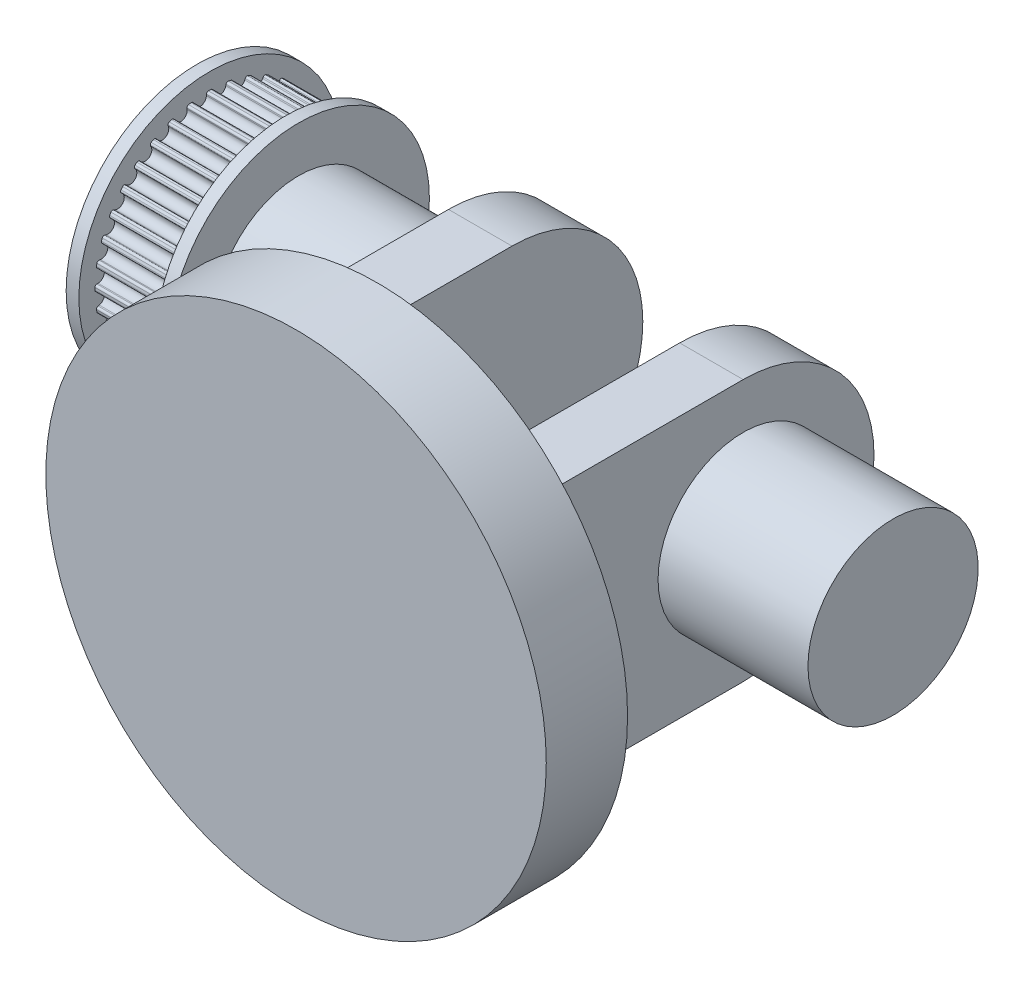
SolidWorks part; units mm, degrees
ref_plane "前视基准面" through (0, 0, 0) normal (0, 0, 1) x (1, 0, 0)
ref_plane "上视基准面" through (0, 0, 0) normal (0, 1, 0) x (1, 0, 0)
ref_plane "右视基准面" through (0, 0, 0) normal (1, 0, 0) x (0, 0, -1)
sketch "Sketch2" plane through (0, 0, 0) normal (0, 0, 1) x (1, 0, 0)
  line L2 (-58, -79.6131) -> (-58, 79.6131)
  line L4 (58, -79.6131) -> (58, 79.6131)
  line L5 (-58, -79.6131) -> (58, 79.6131) construction
  line L6 (-58, 79.6131) -> (58, -79.6131) construction
  arc A0 (-58, -79.6131) -> (58, -79.6131) centre (0, 0) ccw
  arc A1 (58, 79.6131) -> (-58, 79.6131) centre (0, 0) ccw
  dimension "D1" = 197
  dimension "D2" = 116
extrude "Extrude1" add sketch "Sketch2" along normal blind 32
sketch "Sketch3" plane through (-58, 0, 0) normal (-1, 0, 0) x (0, 0, 1)
  line L0 (-86, 0) -> (0, 0) construction
  line L1 (-86, 51.5) -> (0, 51.5)
  line L2 (0, 79.6131) -> (0, -79.6131) construction
  line L3 (0, 51.5) -> (0, -51.5)
  line L4 (0, -51.5) -> (-86, -51.5)
  circle A0 centre (-86, 0) radius 33.5 construction
  arc A1 (-86, 51.5) -> (-86, -51.5) centre (-86, 0) ccw
  dimension "D1" = 67
  dimension "D2" = 103
  dimension "D3" = 86
extrude "Extrude2" add sketch "Sketch3" against normal blind 25
sketch "Sketch4" plane through (-58, 0, 0) normal (-1, 0, 0) x (0, 0, 1)
  circle A0 centre (-86, 0) radius 33.5
  dimension "D1" = 67
extrude "Extrude3" add sketch "Sketch4" along normal blind 59
mirror "Mirror1" about plane through (0, 0, 0) normal (1, 0, 0) of "Extrude2", "Extrude3"
sketch "Sketch5" plane through (-117, 0, 0) normal (1, 0, 0) x (0, 0, -1)
  circle A0 centre (86, 0) radius 51.5
  dimension "D1" = 103
extrude "Extrude4" add sketch "Sketch5" against normal blind 5
sketch "Sketch7" plane through (-122, 0, 0) normal (-1, 0, 0) x (0, 0, 1)
  circle A0 centre (-86, 0) radius 45.15
  dimension "D1" = 90.3
extrude "Extrude5" add sketch "Sketch7" along normal blind 30
sketch "Sketch6" plane through (-122, 0, 0) normal (-1, 0, 0) x (0, 0, 1)
  line L0 (-86, 0) -> (-86, 45.835) construction
  line L1 (-89.9948, 45.6606) -> (-86, 0) construction
  line L2 (-87.2656, 44.3946) -> (-87.2821, 43.9222)
  line L3 (-92.4627, 43.9399) -> (-92.3644, 43.4775)
  circle A0 centre (-86, 0) radius 45.835 construction
  arc A1 (-86.4946, 45.1473) -> (-93.3526, 44.5473) centre (-86, 0) ccw
  arc A2 (-92.3644, 43.4775) -> (-87.2821, 43.9222) centre (-89.8505, 44.0119) ccw
  arc A3 (-86.4946, 45.1473) -> (-87.2656, 44.3946) centre (-86.4861, 44.3673) ccw
  arc A4 (-93.3526, 44.5473) -> (-92.4627, 43.9399) centre (-93.2256, 43.7777) cw
  point P5 (-40.3394, 3.9948)
  point P6 (-41.7268, 11.863)
  point P7 (-44.4594, 19.3707)
  point P8 (-48.4542, 26.2899)
  point P9 (-53.5898, 32.4102)
  point P10 (-59.7101, 37.5458)
  point P11 (-66.6293, 41.5406)
  point P12 (-74.137, 44.2732)
  point P13 (-82.0052, 45.6606)
  point P14 (-89.9948, 45.6606)
  point P15 (-97.863, 44.2732)
  point P16 (-105.3707, 41.5406)
  point P17 (-112.2899, 37.5458)
  point P18 (-118.4102, 32.4102)
  point P19 (-123.5458, 26.2899)
  point P20 (-127.5406, 19.3707)
  point P21 (-130.2732, 11.863)
  point P22 (-131.6606, 3.9948)
  point P23 (-131.6606, -3.9948)
  point P24 (-130.2732, -11.863)
  point P25 (-127.5406, -19.3707)
  point P26 (-123.5458, -26.2899)
  point P27 (-118.4102, -32.4102)
  point P28 (-112.2899, -37.5458)
  point P29 (-105.3707, -41.5406)
  point P30 (-97.863, -44.2732)
  point P31 (-89.9948, -45.6606)
  point P32 (-82.0052, -45.6606)
  point P33 (-74.137, -44.2732)
  point P34 (-66.6293, -41.5406)
  point P35 (-59.7101, -37.5458)
  point P36 (-53.5898, -32.4102)
  point P37 (-48.4542, -26.2899)
  point P38 (-44.4594, -19.3707)
  point P39 (-41.7268, -11.863)
  point P40 (-40.3394, -3.9948)
  dimension "D1" = 91.67
  dimension "D2" = 90.3
  dimension "D3" = 5.14
  dimension "D4" = 3.54
  dimension "D5" = 1.56
  dimension "D6" = 7
extrude "Extrude7" cut sketch "Sketch6" along normal up to surface (30 mm away) up to face at (-152, 0, -40.85)
pattern_circular "CirPattern1" count 36 over 360 about axis through (0, 0, -86) along (1, 0, 0) of "Extrude7"
sketch "Sketch8" plane through (-152, 0, 0) normal (-1, 0, 0) x (0, 0, 1)
  circle A0 centre (-86, 0) radius 51.5
  dimension "D1" = 103
extrude "Extrude8" add sketch "Sketch8" along normal blind 5
sketch "Sketch9" plane through (0, 0, 32) normal (0, 0, 1) x (1, 0, 0)
  line L2 (-58, 79.6131) -> (-58, -79.6131)
  line L4 (58, 79.6131) -> (58, -79.6131)
  arc A0 (-58, 79.6131) -> (-58, -79.6131) centre (0, 0) ccw
  arc A1 (58, -79.6131) -> (58, 79.6131) centre (0, 0) ccw
extrude "Extrude9" add sketch "Sketch9" against normal up to surface (32 mm away) up to face at (0, 0, 0)
